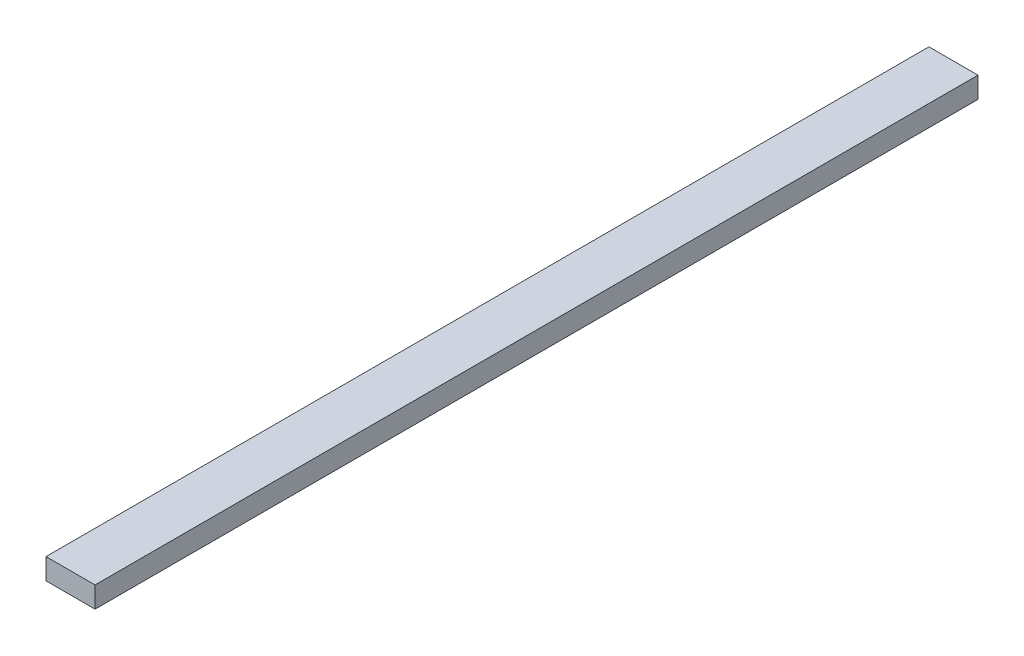
SolidWorks part; units mm, degrees
material "Pine"
ref_plane "Front Plane" through (0, 0, 0) normal (0, 0, 1) x (1, 0, 0)
ref_plane "Top Plane" through (0, 0, 0) normal (0, 1, 0) x (1, 0, 0)
ref_plane "Right Plane" through (0, 0, 0) normal (1, 0, 0) x (0, 0, -1)
sketch "Sketch1" plane through (0, 0, 0) normal (0, 0, 1) x (1, 0, 0)
  line L1 (0, 0) -> (88.9, 0)
  line L2 (0, 0) -> (0, -38.1)
  line L3 (0, -38.1) -> (88.9, -38.1)
  line L4 (88.9, 0) -> (88.9, -38.1)
  dimension "D1" = 88.9
  dimension "D2" = 38.1
extrude "Boss-Extrude1" add sketch "Sketch1" along normal blind 1600.2
equation "\"TableFrontWidth\"=48"
equation "\"TableSideWidth\"=66"
equation "\"LegWidth\"=3.5"
equation "\"LegHeight\"=30"
equation "\"LegDistToBottomStretcher\"=7"
equation "\"BottomStretcherLength\"=\"TableFrontWidth\""
equation "\"SideStretcherLength\"=\"TableSideWidth\"-3"
equation "\"BottomSupportLength\"=\"TableSideWidth\"-3"
equation "\"D1@Boss-Extrude1\"=\"SideStretcherLength\""
equation "\"BottomPlywoodFrontDim\"=\"TableFrontWidth\"-\"LegWidth\"*2-3"
equation "\"BottomPlywoodSideDim\"=\"BottomSupportLength\""
equation "\"TotalBottomSupports\"=4"
equation "\"TotalBottomSupportsLessOne\"=\"TotalBottomSupports\"-1"
equation "\"TotalTopSupports\"=5"
equation "\"TotalTopSupportsLessOne\"=\"TotalTopSupports\"-1"
equation "\"TopSupportSpread\"=\"TableFrontWidth\"-1.5"
equation "\"DistBetweenTopSupports\"=\"TopSupportSpread\"/\"TotalTopSupportsLessOne\""
equation "\"BottomSupportSpread\"= \"BottomPlywoodFrontDim\" - 1.5"
equation "\"DistBetweenBottomSupports\"=\"BottomSupportSpread\"/\"TotalBottomSupportsLessOne\""
